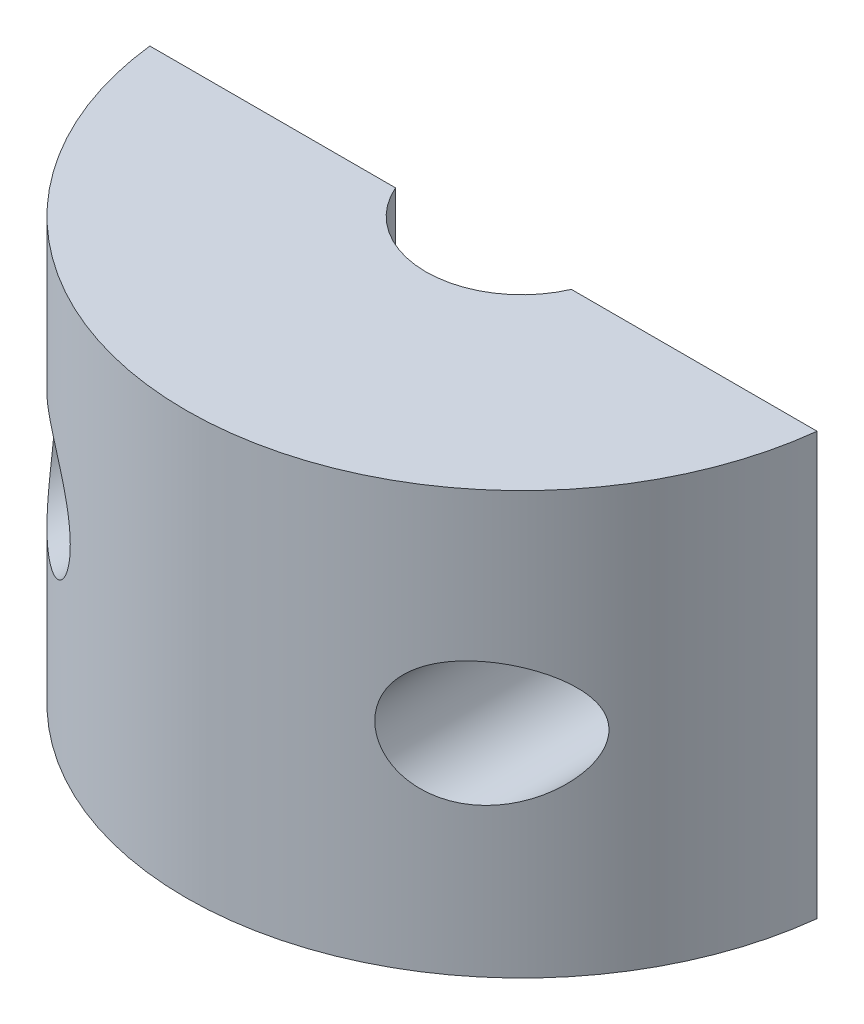
SolidWorks part; units mm, degrees
ref_plane "Front Plane" through (0, 0, 0) normal (0, 0, 1) x (1, 0, 0)
ref_plane "Top Plane" through (0, 0, 0) normal (0, 1, 0) x (1, 0, 0)
ref_plane "Right Plane" through (0, 0, 0) normal (1, 0, 0) x (0, 0, -1)
sketch "Sketch2" plane through (0, 0, 0) normal (0, 1, 0) x (1, 0, 0)
  line L0 (4.899, -1) -> (17.4714, -1)
  line L1 (-4.899, -1) -> (-17.4714, -1)
  arc A0 (-4.899, -1) -> (4.899, -1) centre (0, 0) ccw
  arc A1 (-17.4714, -1) -> (17.4714, -1) centre (0, 0) ccw
  dimension "D1" = 0
  dimension "D2" = 5
  dimension "D3" = 17.5
extrude "Boss-Extrude1" add sketch "Sketch2" along normal blind 22
sketch "Sketch3" plane through (0, 0, 1) normal (0, 0, -1) x (-1, 0, 0)
  line L0 (11.1852, 22) -> (11.1852, 0) construction
  line L1 (4.899, 22) -> (17.4714, 22) construction
  line L2 (4.899, 0) -> (17.4714, 0) construction
  line L3 (-11.1852, 0) -> (-11.1852, 22) construction
  line L4 (-17.4714, 0) -> (-4.899, 0) construction
  line L5 (-17.4714, 22) -> (-4.899, 22) construction
  circle A0 centre (11.1852, 11) radius 1.75
  circle A1 centre (-11.1852, 11) radius 1.75
  dimension "D1" = 3.5
extrude "Cut-Extrude1" cut sketch "Sketch3" against normal blind 22
ref_plane "Plane1" through (0, 0, 5) normal (0, 0, -1) x (-1, 0, 0)
sketch "Sketch4" plane through (0, 0, 5) normal (0, 0, -1) x (-1, 0, 0)
  circle A0 centre (-11.1852, 11) radius 3.25
  circle A1 centre (11.1852, 11) radius 3.25
  dimension "D1" = 6.5
extrude "Cut-Extrude2" cut sketch "Sketch4" against normal blind 22
sketch "Sketch5" plane through (0, 22, 0) normal (0, 1, 0) x (1, 0, 0)
  line L1 (-17.4714, -1) -> (17.7597, -1)
  line L2 (-17.4714, -1) -> (-17.4714, -2)
  line L3 (-17.4714, -2) -> (17.7597, -2)
  line L4 (17.7597, -1) -> (17.7597, -2)
  dimension "D1" = 1
extrude "Cut-Extrude3" cut sketch "Sketch5" against normal blind 22
